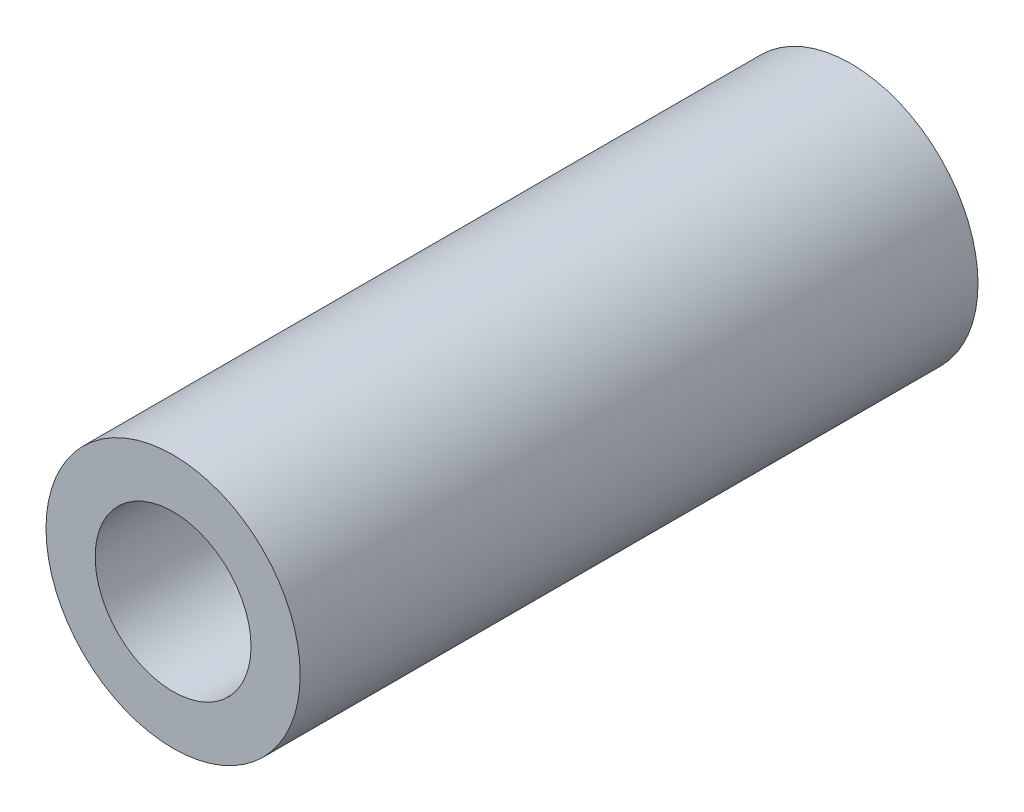
SolidWorks part; units mm, degrees
ref_plane "Front Plane" through (0, 0, 0) normal (0, 0, 1) x (1, 0, 0)
ref_plane "Top Plane" through (0, 0, 0) normal (0, 1, 0) x (1, 0, 0)
ref_plane "Right Plane" through (0, 0, 0) normal (1, 0, 0) x (0, 0, -1)
sketch "Sketch1" plane through (0, 0, 0) normal (0, 0, 1) x (1, 0, 0)
  circle A0 centre (0, 0) radius 2.3812
  circle A1 centre (0, 0) radius 1.4605
  dimension "OD" = 4.7625
  dimension "ID" = 2.921
extrude "Extrude1" add sketch "Sketch1" along normal mid plane 12.7
sketch "Sketch2" plane through (0, 0, 0) normal (1, 0, 0) x (0, 0, -1)
  line L0 (-6.35, -1.4605) -> (6.35, -1.4605) construction
  line L3 (6.35, 1.4605) -> (-6.35, 1.4605) construction
  line L5 (-6.35, -1.4605) -> (6.35, -1.4605)
  line L6 (6.35, 1.4605) -> (-6.35, 1.4605)
sketch "Sketch4" plane through (0, 0, 6.35) normal (0, 0, 1) x (1, 0, 0)
  line L0 (0, 0) -> (-1.0327, 1.0327)
  line L1 (0, -2.6194) -> (0, 2.6194) construction
  circle A0 centre (0, 0) radius 1.4605 construction
  dimension "D1" = 45
